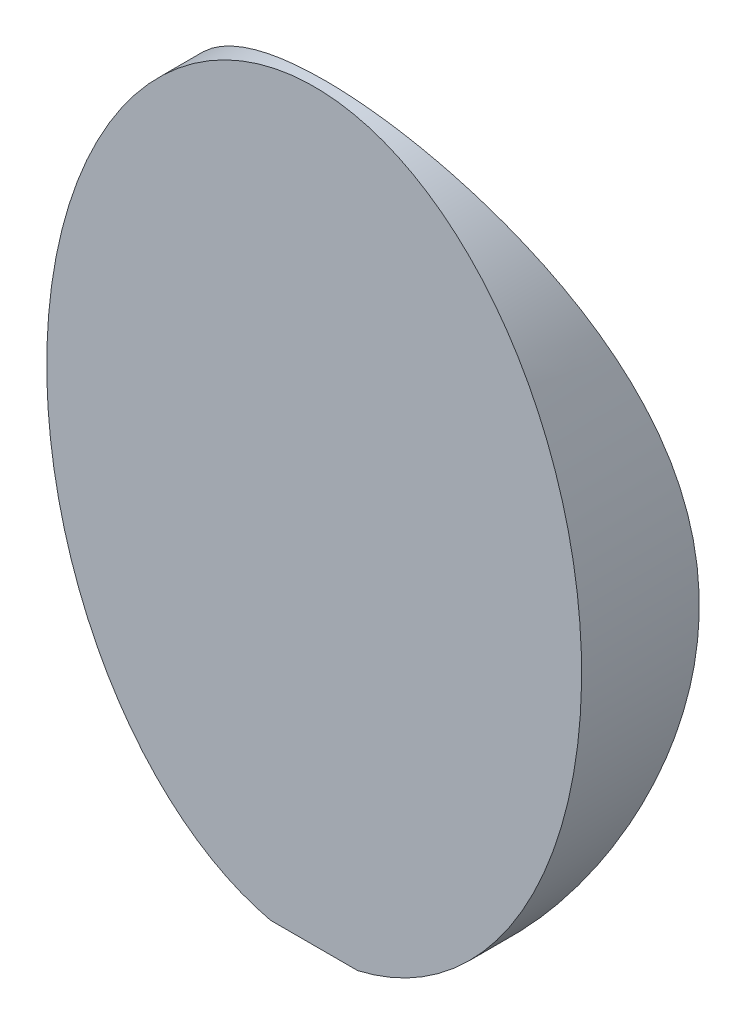
SolidWorks part; units mm, degrees
material "PE High Density"
ref_plane "Front Plane" through (0, 0, 0) normal (0, 0, 1) x (1, 0, 0)
ref_plane "Top Plane" through (0, 0, 0) normal (0, 1, 0) x (1, 0, 0)
ref_plane "Right Plane" through (0, 0, 0) normal (1, 0, 0) x (0, 0, -1)
sketch "Sketch1" plane through (0, 0, 0) normal (0, 0, 1) x (1, 0, 0)
  line L0 (-0.0815, -0.6906) -> (0.0815, -0.6906)
  ellipse E0 centre (0, 0) end of major axis (0, 0.7) minor radius 0.5 (0.0815, -0.6906) -> (-0.0815, -0.6906) ccw
  dimension "D1" = 1.4
  dimension "D2" = 1
extrude "Boss-Extrude1" add sketch "Sketch1" along normal blind 0.4 contours E0 L0
sketch "Sketch2" plane through (0, 0, 0) normal (0, 1, 0) x (1, 0, 0)
  line L2 (-0.5, -0.18) -> (-0.5, 0.0376)
  line L3 (-0.5, 0.0376) -> (0.5, 0.0376)
  line L4 (0.5, 0.0376) -> (0.5, -0.18)
  line L5 (-0.5, 0) -> (-0.5, -0.4) construction
  line L6 (-0.5, -0.38) -> (0.5, -0.38) construction
  line L7 (0.5, -0.4) -> (0.5, 0) construction
  line L8 (0.5, -0.18) -> (0.5, -0.38) construction
  line L9 (-0.5, -0.38) -> (-0.5, -0.18) construction
  line L10 (-0.5, -0.4) -> (0.5, -0.4) construction
  arc A1 (-0.5, -0.18) -> (0.5, -0.18) centre (0, 0.345) ccw
  dimension "D1" = 0.2
  dimension "D2" = 0.02
extrude "Cut-Extrude1" cut sketch "Sketch2" against normal through all both and the other way through all
